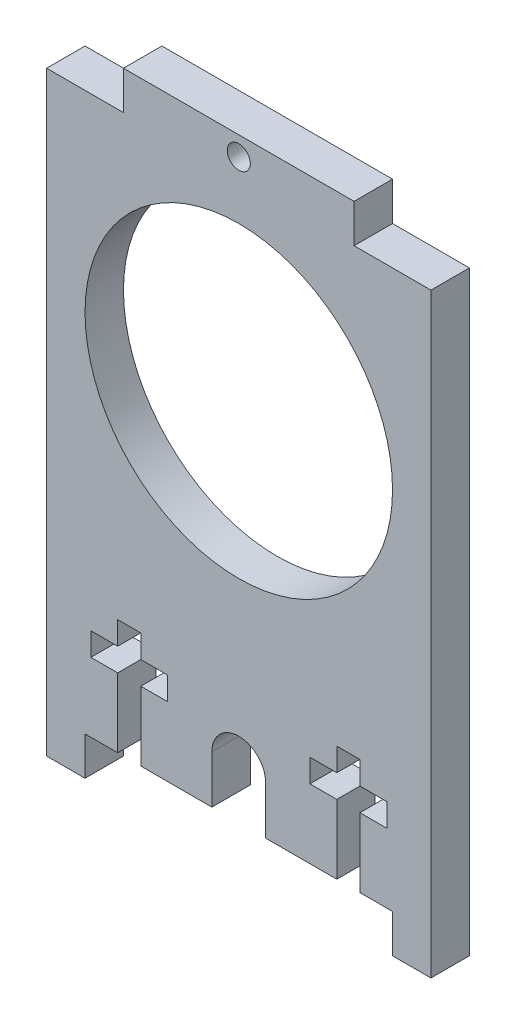
SolidWorks part; units mm, degrees
material "CA"
ref_plane "Alzado" through (0, 0, 0) normal (0, 0, 1) x (1, 0, 0)
ref_plane "Planta" through (0, 0, 0) normal (0, 1, 0) x (1, 0, 0)
ref_plane "Vista lateral" through (0, 0, 0) normal (1, 0, 0) x (0, 0, -1)
sketch "Croquis1" plane through (0, 0, 0) normal (0, 0, 1) x (1, 0, 0)
  line L0 (0, 0) -> (5, 0)
  line L1 (5, 0) -> (5, 5)
  line L2 (5, 5) -> (9.25, 5)
  line L3 (9.25, 5) -> (9.25, 14)
  line L4 (9.25, 14) -> (5.75, 14)
  line L5 (5.75, 14) -> (5.75, 17)
  line L6 (5.75, 17) -> (9.25, 17)
  line L7 (9.25, 17) -> (9.25, 20)
  line L8 (9.25, 20) -> (12.25, 20)
  line L9 (12.25, 20) -> (12.25, 17)
  line L10 (12.25, 17) -> (15.75, 17)
  line L11 (15.75, 17) -> (15.75, 14)
  line L12 (15.75, 14) -> (12.25, 14)
  line L13 (12.25, 14) -> (12.25, 5)
  line L14 (12.25, 5) -> (21.5, 5)
  line L15 (21.5, 5) -> (21.5, 11.24)
  line L16 (0, 0) -> (0, 77.5)
  line L17 (0, 77.5) -> (10, 77.5)
  line L18 (10, 77.5) -> (10, 82.5)
  line L19 (10, 82.5) -> (40, 82.5)
  line L21 (28.5, 5) -> (28.5, 11.24)
  line L22 (37.75, 5) -> (28.5, 5)
  line L23 (37.75, 14) -> (37.75, 5)
  line L24 (34.25, 14) -> (37.75, 14)
  line L25 (34.25, 17) -> (34.25, 14)
  line L26 (37.75, 17) -> (34.25, 17)
  line L27 (37.75, 20) -> (37.75, 17)
  line L28 (40.75, 20) -> (37.75, 20)
  line L29 (40.75, 17) -> (40.75, 20)
  line L30 (44.25, 17) -> (40.75, 17)
  line L31 (44.25, 14) -> (44.25, 17)
  line L32 (40.75, 14) -> (44.25, 14)
  line L33 (40.75, 5) -> (40.75, 14)
  line L34 (45, 5) -> (40.75, 5)
  line L35 (45, 0) -> (45, 5)
  line L36 (50, 0) -> (45, 0)
  line L37 (40, 77.5) -> (40, 82.5)
  line L38 (50, 77.5) -> (40, 77.5)
  line L39 (50, 0) -> (50, 77.5)
  arc A0 (21.5, 11.24) -> (28.5, 11.24) centre (25, 11.24) cw
  circle A1 centre (25, 80) radius 1.5
  circle A2 centre (25, 52.5) radius 20
  point P23 (25, 82.5)
  dimension "D20" = 3.5
  dimension "D22" = 3
  dimension "D25" = 40
  dimension "D1" = 5
  dimension "D2" = 5
  dimension "D3" = 4.25
  dimension "D4" = 9
  dimension "D5" = 3.5
  dimension "D6" = 3
  dimension "D7" = 3.5
  dimension "D8" = 3
  dimension "D9" = 3
  dimension "D10" = 3
  dimension "D11" = 3.5
  dimension "D12" = 3
  dimension "D13" = 3.5
  dimension "D14" = 9
  dimension "D15" = 9.25
  dimension "D16" = 6.24
  dimension "D17" = 77.5
  dimension "D18" = 10
  dimension "D19" = 30
  dimension "D21" = 5
  dimension "D23" = 5
  dimension "D24" = 77.5
  dimension "D26" = 2.5
extrude "Saliente-Extruir1" add sketch "Croquis1" along normal blind 5
